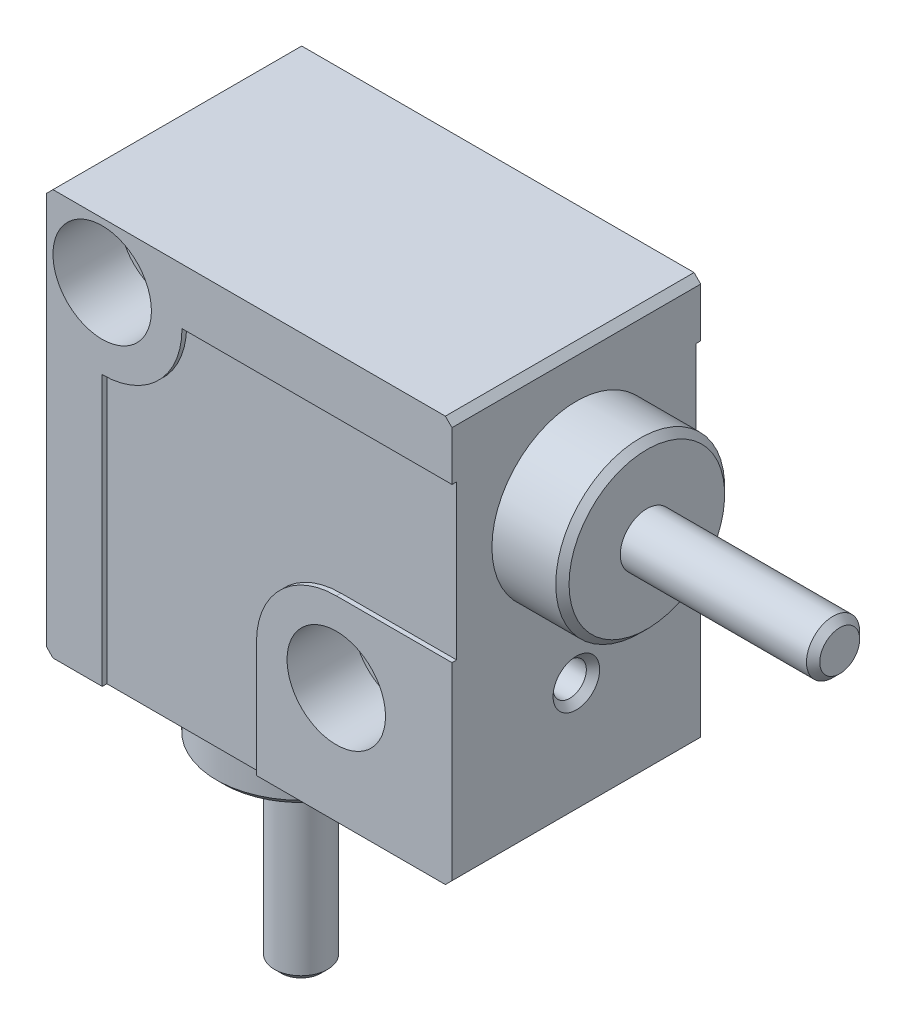
SolidWorks part; units mm, degrees
ref_plane "Face" through (0, 0, 0) normal (0, 0, 1) x (1, 0, 0)
ref_plane "Dessus" through (0, 0, 0) normal (0, 1, 0) x (1, 0, 0)
ref_plane "Droite" through (0, 0, 0) normal (1, 0, 0) x (0, 0, -1)
sketch "Esquisse1" plane through (0, 0, 0) normal (0, 0, 1) x (1, 0, 0)
  line L1 (-15.25, -15.25) -> (15.25, -15.25)
  line L2 (-15.25, -15.25) -> (-15.25, 15.25)
  line L3 (-15.25, 15.25) -> (15.25, 15.25)
  line L4 (15.25, -15.25) -> (15.25, 15.25)
  line L5 (-15.25, -15.25) -> (15.25, 15.25) construction
  line L6 (-15.25, 15.25) -> (15.25, -15.25) construction
  point P0 (0, 0)
  dimension "D1" = 30.5
extrude "Boss.-Extru.1" add sketch "Esquisse1" along normal mid plane 18.7
sketch "Esquisse2" plane through (0, 0, 0) normal (0, 0, 1) x (1, 0, 0)
  line L0 (15.25, 5.45) -> (56.666, 5.45) construction
  line L1 (15.25, -15.25) -> (15.25, 15.25) construction
  line L2 (35.05, 5.45) -> (35.05, 7.45)
  line L3 (35.05, 7.45) -> (20.55, 7.45)
  line L4 (20.55, 7.45) -> (20.55, 11.8)
  line L5 (20.55, 11.8) -> (15.25, 11.8)
  line L6 (-15.25, -15.25) -> (15.25, -15.25) construction
  line L7 (15.25, 11.8) -> (15.25, 5.45)
  line L8 (15.25, 5.45) -> (35.05, 5.45)
  dimension "D1" = 12.7
  dimension "D2" = 5.3
  dimension "D3" = 4
  dimension "D4" = 19.8
  dimension "D5" = 20.7
revolve "Révolution1" add sketch "Esquisse2" angle 360 about L0
sketch "Esquisse3" plane through (0, 0, 0) normal (0, 0, 1) x (1, 0, 0)
  line L0 (-5.45, -15.25) -> (-5.45, -35.4331) construction
  line L1 (-15.25, -15.25) -> (15.25, -15.25) construction
  line L2 (-5.45, -35.05) -> (-7.45, -35.05)
  line L3 (-7.45, -35.05) -> (-7.45, -20.55)
  line L4 (-7.45, -20.55) -> (-11.8, -20.55)
  line L5 (-11.8, -20.55) -> (-11.8, -15.25)
  line L6 (-15.25, -15.25) -> (15.25, -15.25) construction
  line L7 (-11.8, -15.25) -> (-5.45, -15.25)
  line L8 (15.25, -15.25) -> (15.25, 15.25) construction
  line L9 (-5.45, -15.25) -> (-5.45, -35.05)
  dimension "D1" = 12.7
  dimension "D2" = 20.7
  dimension "D3" = 5.3
  dimension "D4" = 19.8
  dimension "D5" = 4
revolve "Révolution2" add sketch "Esquisse3" angle 360 about L0
hole_wizard "Trou taraudé M31" positions "Esquisse5" profile "Esquisse4" tap size "M3" standard "ISO"
sketch "Esquisse5" plane through (15.25, 0, 0) normal (1, 0, 0) x (0, 0, -1)
  line L0 (0, -6.55) -> (0, 0) construction
  circle A0 centre (0, 5.45) radius 2 construction
  point P0 (0, -6.55)
  dimension "D1" = 12
sketch "Esquisse4" plane through (15.25, -6.55, 0) normal (0, 1, 0) x (0, 0, -1)
  line L0 (0, 0) -> (0, 9.2511)
  line L1 (0, 9.2511) -> (1.25, 8.5)
  line L2 (1.25, 8.5) -> (1.25, 0)
  line L5 (1.25, 0) -> (0, 0)
  line L10 (0, 9.2511) -> (-1.25, 8.5) construction
  line L11 (0, -6.35) -> (0, 107.95) construction
  dimension "Diamètre du trou pour taraudage" = 2.5
  dimension "Profondeur du trou pour taraudage" = 8.5
  dimension "Angle de pointe" = 118
cosmetic thread "Filetage de perçage1" parameters "D1"=6, "D2"=3
hole_wizard "Trou taraudé M32" positions "Esquisse7" profile "Esquisse6" tap size "M3" standard "ISO"
sketch "Esquisse7" plane through (0, -15.25, 0) normal (0, -1, 0) x (-1, 0, 0)
  line L0 (-6.55, 0) -> (0, 0) construction
  circle A0 centre (5.45, 0) radius 2 construction
  point P0 (-6.55, 0)
  dimension "D1" = 12
sketch "Esquisse6" plane through (6.55, -15.25, 0) normal (1, 0, 0) x (0, 0, -1)
  line L0 (0, 0) -> (0, 9.2511)
  line L1 (0, 9.2511) -> (1.25, 8.5)
  line L2 (1.25, 8.5) -> (1.25, 0)
  line L5 (1.25, 0) -> (0, 0)
  line L10 (0, 9.2511) -> (-1.25, 8.5) construction
  line L11 (0, -6.35) -> (0, 107.95) construction
  dimension "Diamètre du trou pour taraudage" = 2.5
  dimension "Profondeur du trou pour taraudage" = 8.5
  dimension "Angle de pointe" = 118
cosmetic thread "Filetage de perçage2" parameters "D1"=6, "D2"=3
hole_wizard "Perçage1" positions "Esquisse9" profile "Esquisse8" legacy end condition through all
sketch "Esquisse9" plane through (0, 0, -9.35) normal (0, 0, -1) x (-1, 0, 0)
  line L0 (-15.25, -15.25) -> (-15.25, 15.25) construction
  line L2 (15.25, -15.25) -> (-15.25, -15.25) construction
  point P0 (11.05, 11.05)
  point P2 (-6.55, -6.55)
  dimension "D1" = 26.3
  dimension "D2" = 17.6
  dimension "D3" = 26.3
  dimension "D4" = 17.6
sketch "Esquisse8" plane through (-11.05, 11.05, -9.35) normal (1, 0, 0) x (0, 1, 0)
  line L0 (0, 0) -> (0, 19.8116)
  line L1 (0, 19.8116) -> (1.85, 18.7)
  line L2 (1.85, 18.7) -> (1.85, 5)
  line L3 (1.85, 5) -> (3.7, 5)
  line L4 (3.7, 0) -> (0, 0)
  line L5 (0, -11.3109) -> (0, 121.1557) construction
  line L6 (0, 19.8116) -> (-1.85, 18.7) construction
  line L7 (3.7, 5) -> (3.7, 0)
  dimension "Diamètre" = 3.7
  dimension "Profondeur" = 18.7
  dimension "Diamètre chambrage" = 7.4
  dimension "Profondeur chambrage" = 5
  dimension "Angle" = 118
sketch "Esquisse10" plane through (0, 0, -9.35) normal (0, 0, 1) x (1, 0, 0)
  line L0 (15.25, 11.05) -> (-5.05, 11.05)
  line L1 (15.25, -15.25) -> (15.25, 15.25) construction
  line L2 (-11.05, 5.05) -> (-11.05, -15.25)
  line L3 (-15.25, -15.25) -> (15.25, -15.25) construction
  line L4 (-11.05, -15.25) -> (0.55, -15.25)
  line L5 (15.25, -0.55) -> (15.25, 11.05)
  line L6 (0.55, -15.25) -> (0.55, -6.55)
  line L7 (15.25, -0.55) -> (6.55, -0.55)
  line L8 (-11.05, 5.05) -> (-20.4276, 5.05) construction
  arc A0 (-5.05, 11.05) -> (-11.05, 5.05) centre (-11.05, 11.05) cw
  arc A1 (6.55, -0.55) -> (0.55, -6.55) centre (6.55, -6.55) ccw
  circle A4 centre (-11.05, 11.05) radius 3.7 construction
  circle A5 centre (6.55, -6.55) radius 3.7 construction
  dimension "D1" = 6
  dimension "D2" = 6
extrude "Enlèv. mat.-Extru.3" cut sketch "Esquisse10" along normal blind 0.35
mirror "Symétrie1" about plane through (0, 0, 0) normal (0, 0, 1) of "Enlèv. mat.-Extru.3", "Perçage1"
chamfer "Chanfrein1" distance 0.5 angle 45 10 edges at (35.05, 5.45, 2) (20.55, 5.45, 6.35) (-7.45, -35.05, 0) (-11.8, -20.55, 0) (-15.25, -15.25, 0) (-15.25, 15.25, 0) (15.25, 15.25, 0) (15.25, -15.25, 0) (6.55, -15.25, -1.25) (15.25, -6.55, -1.25)
